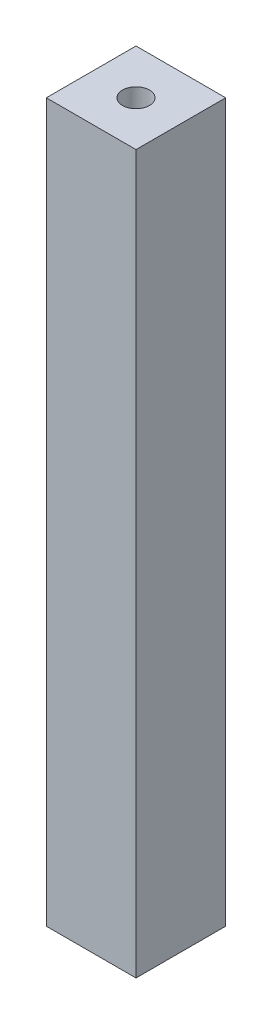
SolidWorks part; units mm, degrees
ref_plane "正面" through (0, 0, 0) normal (0, 0, 1) x (1, 0, 0)
ref_plane "平面" through (0, 0, 0) normal (0, 1, 0) x (1, 0, 0)
ref_plane "右側面" through (0, 0, 0) normal (1, 0, 0) x (0, 0, -1)
sketch "ｽｹｯﾁ1" plane through (0, 0, 0) normal (0, 1, 0) x (1, 0, 0)
  line L1 (-5, -5) -> (5, -5)
  line L2 (-5, -5) -> (-5, 5)
  line L3 (-5, 5) -> (5, 5)
  line L4 (5, -5) -> (5, 5)
  line L5 (-5, -5) -> (5, 5) construction
  line L6 (-5, 5) -> (5, -5) construction
  point P0 (0, 0)
  dimension "D1" = 10
extrude "ﾎﾞｽ - 押し出し1" add sketch "ｽｹｯﾁ1" along normal blind 80
sketch "ｽｹｯﾁ2" plane through (0, 0, 0) normal (0, 1, 0) x (1, 0, 0)
  circle A0 centre (0, 0) radius 1.5
  dimension "D1" = 3
extrude "ｶｯﾄ - 押し出し2" cut sketch "ｽｹｯﾁ2" along normal through all
